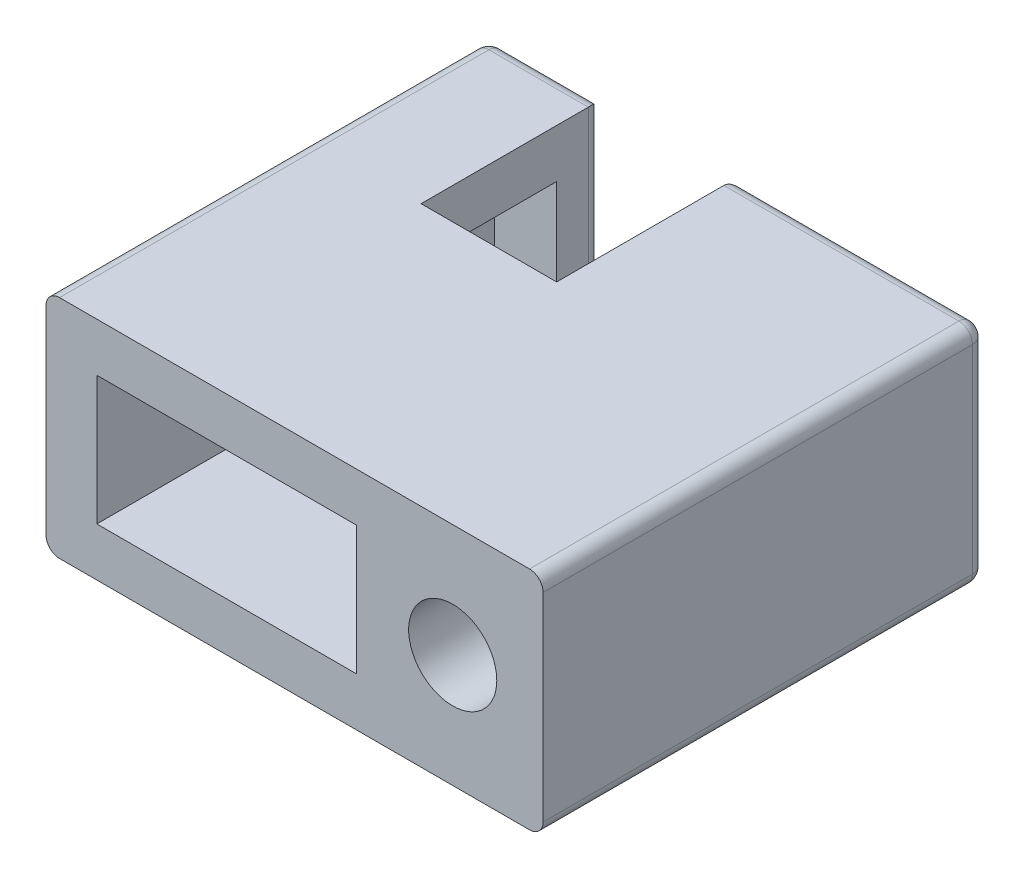
SolidWorks part; units mm, degrees
ref_plane "Front Plane" through (0, 0, 0) normal (0, 0, 1) x (1, 0, 0)
ref_plane "Top Plane" through (0, 0, 0) normal (0, 1, 0) x (1, 0, 0)
ref_plane "Right Plane" through (0, 0, 0) normal (1, 0, 0) x (0, 0, -1)
sketch "Sketch1" plane through (0, 0, 0) normal (0, 0, 1) x (1, 0, 0)
  line L1 (-4, 1.175) -> (7, 1.175)
  line L2 (-4, 1.175) -> (-4, -3.825)
  line L3 (-4, -3.825) -> (7, -3.825)
  line L4 (7, 1.175) -> (7, -3.825)
  line L5 (2.875, 0.1) -> (-2.875, 0.1)
  line L6 (-2.775, -2.65) -> (-2.775, 0) construction
  line L8 (7, -1.325) -> (5, -1.325) construction
  line L9 (-2.875, -2.75) -> (-2.875, 0.1)
  line L10 (2.775, -2.65) -> (2.775, 0) construction
  line L11 (2.775, 0) -> (-2.775, 0) construction
  line L12 (2.775, -2.65) -> (-2.775, -2.65) construction
  line L13 (2.775, 0) -> (-2.775, 0) construction
  line L14 (2.775, -2.65) -> (2.775, 0) construction
  line L15 (2.775, -2.65) -> (-2.775, -2.65) construction
  line L16 (-2.775, -2.65) -> (-2.775, 0) construction
  line L17 (2.875, -2.75) -> (-2.875, -2.75)
  line L18 (2.875, -2.75) -> (2.875, 0.1)
  line L19 (-4, -1.325) -> (0, -1.325) construction
  line L20 (-2.875, 0.1) -> (2.875, -2.75) construction
  circle A0 centre (5, -1.325) radius 0.975
  dimension "D3" = 1.95
  dimension "D1" = 5
  dimension "D2" = 0.1
  dimension "D4" = 11
  dimension "D5" = 2
  dimension "D6" = 4
extrude "Boss-Extrude1" add sketch "Sketch1" against normal offset from surface 1 and the other way blind 4
sketch "Sketch3" plane through (0, -2.75, 0) normal (0, 1, 0) x (1, 0, 0)
  line L0 (2.875, 5.8) -> (-2.875, 5.8) construction
  line L1 (-1.5, 5.8) -> (1.5, 5.8)
  line L2 (-1.5, 5.8) -> (-1.5, 1.8)
  line L3 (-1.5, 1.8) -> (1.5, 1.8)
  line L4 (1.5, 5.8) -> (1.5, 1.8)
extrude "Cut-Extrude1" cut sketch "Sketch3" against normal through all both and the other way through all
sketch "Sketch4" plane through (0, 0, -5.8) normal (0, 0, -1) x (-1, 0, 0)
  line L1 (-2.875, 0.1) -> (-1.5, 0.1)
  line L2 (-2.875, 0.1) -> (-2.875, -2.75)
  line L3 (-2.875, -2.75) -> (-1.5, -2.75)
  line L4 (-1.5, 0.1) -> (-1.5, -2.75)
  line L5 (2.875, 0.1) -> (1.5, 0.1)
  line L6 (2.875, 0.1) -> (2.875, -2.75)
  line L7 (2.875, -2.75) -> (1.5, -2.75)
  line L8 (1.5, 0.1) -> (1.5, -2.75)
extrude "Boss-Extrude3" add sketch "Sketch4" against normal up to surface (1 mm away)
fillet "Fillet1" radius 0.3 4 edges at (7, 1.175, -0.9) (7, -3.825, -0.9) (-4, -3.825, -0.9) (-4, 1.175, -0.9)
fillet "Fillet2" radius 0.3 13 edges at (5.975, -1.325, -5.8) (1.5, -1.325, -5.8) (4.1, -3.825, -5.8) (6.9121, -3.7371, -5.8) (7, -1.325, -5.8) (6.9121, 1.0871, -5.8) (4.1, 1.175, -5.8) (-1.5, -1.325, -5.8) (-2.6, 1.175, -5.8) (-3.9121, 1.0871, -5.8) (-4, -1.325, -5.8) (-3.9121, -3.7371, -5.8) (-2.6, -3.825, -5.8)
